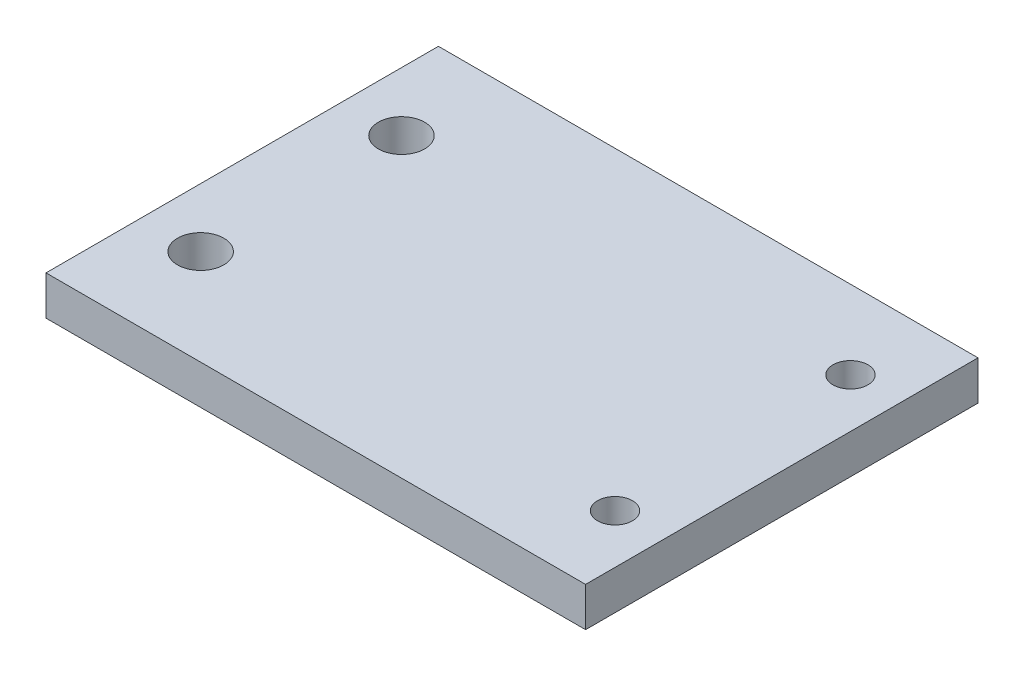
SolidWorks part; units mm, degrees
ref_plane "Front" through (0, 0, 0) normal (0, 0, 1) x (1, 0, 0)
ref_plane "Top" through (0, 0, 0) normal (0, 1, 0) x (1, 0, 0)
ref_plane "Right" through (0, 0, 0) normal (1, 0, 0) x (0, 0, -1)
sketch "Sketch1" plane through (0, 0, 0) normal (0, 1, 0) x (1, 0, 0)
  line L1 (0, 0) -> (34.925, 0)
  line L2 (0, 0) -> (0, 25.4)
  line L3 (0, 25.4) -> (34.925, 25.4)
  line L4 (34.925, 0) -> (34.925, 25.4)
  dimension "D1" = 25.4
  dimension "D2" = 34.925
extrude "Boss-Extrude1" add sketch "Sketch1" along normal blind 2.54
sketch "Sketch2" plane through (0, 2.54, 0) normal (0, 1, 0) x (1, 0, 0)
  line L0 (0, 12.7) -> (34.925, 12.7) construction
  line L1 (0, 25.4) -> (0, 0) construction
  line L2 (34.925, 0) -> (34.925, 25.4) construction
  circle A0 centre (3.81, 19.2) radius 1.5
  circle A1 centre (3.81, 6.2) radius 1.5
  dimension "D1" = 3
  dimension "D2" = 6.5
  dimension "D3" = 3.81
extrude "Cut-Extrude3" cut sketch "Sketch2" along normal through all and the other way through all
sketch "Sketch5" plane through (0, 2.54, 0) normal (0, 1, 0) x (1, 0, 0)
  line L0 (0, 12.7) -> (34.925, 12.7) construction
  line L1 (0, 25.4) -> (0, 0) construction
  line L2 (34.925, 0) -> (34.925, 25.4) construction
  line L3 (34.925, 25.4) -> (0, 25.4) construction
  circle A0 centre (31.75, 20.32) radius 1.1303
  circle A1 centre (31.75, 5.08) radius 1.1303
  dimension "D1" = 2.2606
  dimension "D2" = 5.08
  dimension "D3" = 3.175
extrude "Cut-Extrude4" cut sketch "Sketch5" against normal through all
